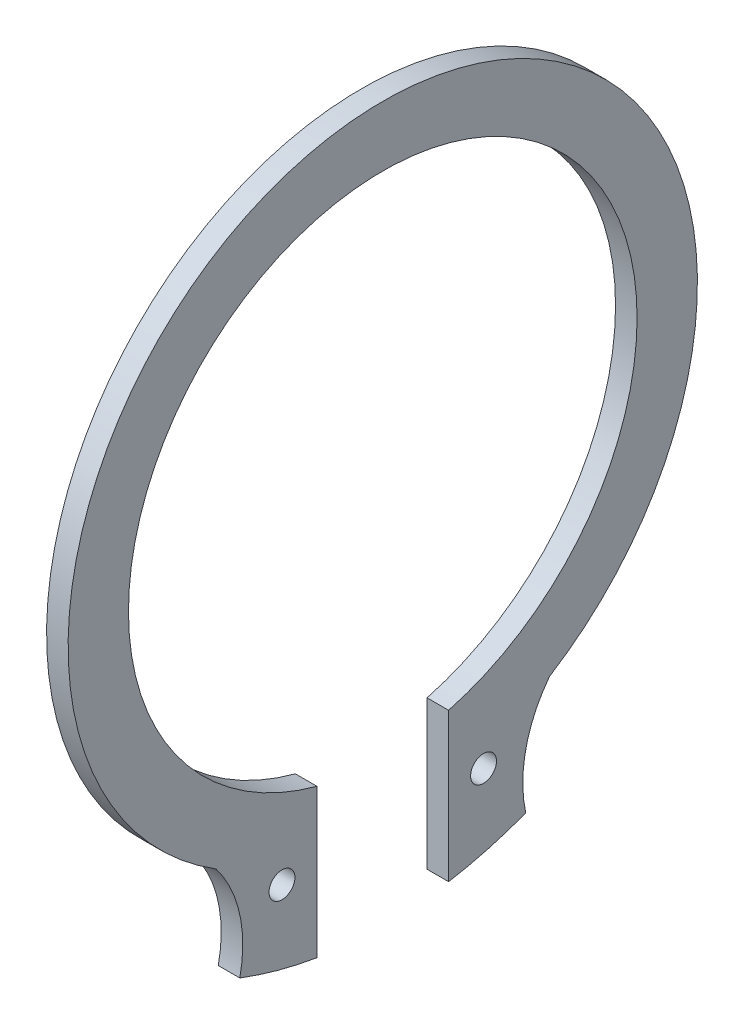
SolidWorks part; units mm, degrees
ref_plane "Front" through (0, 0, 0) normal (0, 0, 1) x (1, 0, 0)
ref_plane "Top" through (0, 0, 0) normal (0, 1, 0) x (1, 0, 0)
ref_plane "Right" through (0, 0, 0) normal (1, 0, 0) x (0, 0, -1)
sketch "Esquisse1" plane through (0, 0, 0) normal (1, 0, 0) x (0, 0, -1)
  line L0 (0, 0) -> (-7.6352, -28.4948) construction
  line L1 (0, 0) -> (0, -81.578) construction
  line L2 (-7.6352, -28.4948) -> (-7.6352, -45.7168)
  line L3 (7.6352, -28.4948) -> (7.6352, -45.7168)
  arc A0 (-16.585, -43.2812) -> (-7.6352, -45.7168) centre (0, 0) ccw
  arc A1 (7.6352, -28.4948) -> (-7.6352, -28.4948) centre (0, 0) ccw
  arc A2 (19.3383, -30.9561) -> (-19.3383, -30.9561) centre (0, 0) ccw
  arc A4 (16.585, -43.2812) -> (7.6352, -45.7168) centre (0, 0) cw
  circle A5 centre (0, 0) radius 36.5 construction
  arc A6 (-16.585, -43.2812) -> (-19.3383, -30.9561) centre (-31.2405, -40.0851) ccw
  arc A7 (16.585, -43.2812) -> (19.3383, -30.9561) centre (31.2405, -40.0851) cw
  circle A8 centre (0, 0) radius 29.5 construction
  circle A9 centre (-11.6902, -36.3643) radius 1.5
  circle A10 centre (11.6902, -36.3643) radius 1.5
  point P11 (16.585, -43.2812)
  point P12 (-16.585, -43.2812)
  point P19 (-21.5105, -36.3643)
  point P20 (11.6902, -36.3643)
  point P22 (21.5105, -36.3643)
  dimension "D1" = 92.7
  dimension "D2" = 59
  dimension "D4" = 3
  dimension "D5" = 15
  dimension "D6" = 15
  dimension "D3" = 7
extrude "Boss.-Extru.1" add sketch "Esquisse1" along normal blind 2.5
